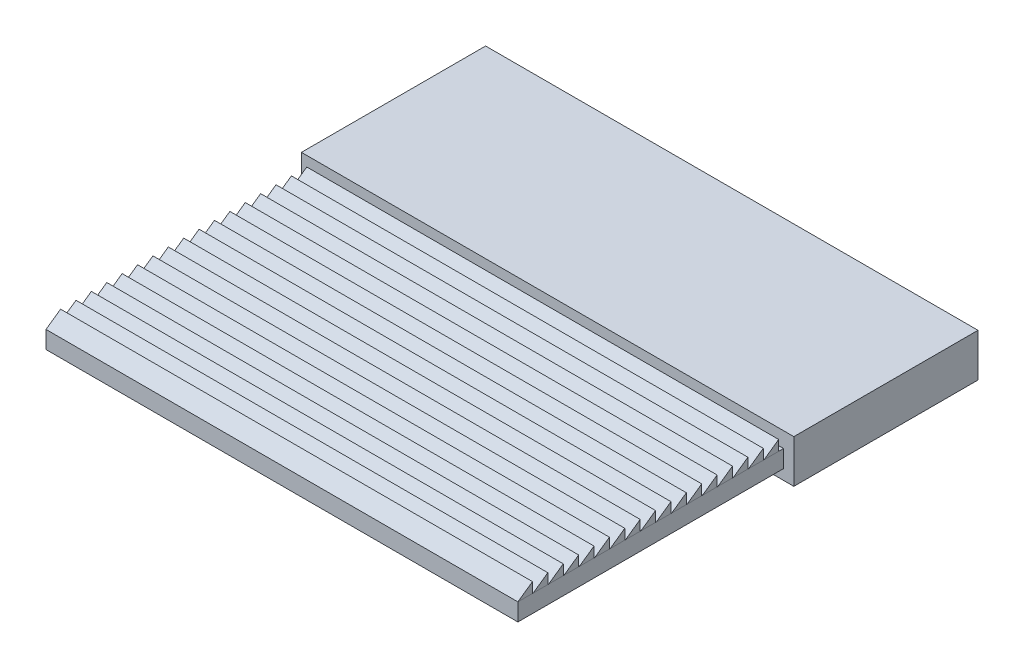
SolidWorks part; units mm, degrees
ref_plane "Front Plane" through (0, 0, 0) normal (0, 0, 1) x (1, 0, 0)
ref_plane "Top Plane" through (0, 0, 0) normal (0, 1, 0) x (1, 0, 0)
ref_plane "Right Plane" through (0, 0, 0) normal (1, 0, 0) x (0, 0, -1)
sketch "Sketch1" plane through (0, 0, 0) normal (0, 1, 0) x (1, 0, 0)
  line L1 (-98.1766, -77.3984) -> (141.8234, -77.3984)
  line L2 (-98.1766, -77.3984) -> (-98.1766, 273.7516)
  line L3 (-98.1766, 273.7516) -> (141.8234, 273.7516)
  line L4 (141.8234, -77.3984) -> (141.8234, 273.7516)
  dimension "D1" = 351.15
  dimension "D2" = 240
extrude "Boss-Extrude3" add sketch "Sketch1" along normal blind 21
sketch "Sketch4" plane through (0, 21, 0) normal (0, 1, 0) x (1, 0, 0)
  line L0 (-98.1766, 54.4816) -> (141.8234, 54.4816)
  line L1 (-98.1766, 273.7516) -> (-98.1766, -77.3984) construction
  line L2 (141.8234, -77.3984) -> (141.8234, 273.7516) construction
  line L3 (-98.1766, -77.3984) -> (141.8234, -77.3984) construction
  line L4 (-98.1766, 183.9816) -> (141.8234, 183.9816)
  line L5 (-98.1766, 183.9816) -> (-98.1766, 54.4816)
  line L6 (141.8234, 54.4816) -> (141.8234, 183.9816)
  dimension "D1" = 131.88
  dimension "D2" = 129.5
ref_plane "Plane4" through (0, 0, -54.4816) normal (0, 0, -1) x (-1, 0, 0)
sketch "Sketch5" plane through (0, 0, -54.4816) normal (0, 0, -1) x (-1, 0, 0)
  line L1 (-145.3358, 60.6964) -> (103.6401, 60.6964)
  line L2 (-145.3358, 60.6964) -> (-145.3358, -52.4745)
  line L3 (-145.3358, -52.4745) -> (103.6401, -52.4745)
  line L4 (103.6401, 60.6964) -> (103.6401, -52.4745)
extrude "Cut-Extrude2" cut sketch "Sketch5" against normal blind 513
extrude "Cut-Extrude3" cut sketch "Sketch4" against normal blind 7.5
sketch "Sketch6" plane through (0, 0, 0) normal (0, -1, 0) x (1, 0, 0)
  line L4 (141.8234, -54.4816) -> (-98.1766, -54.4816)
  line L5 (141.8234, -183.9816) -> (141.8234, -54.4816)
  line L6 (-98.1766, -183.9816) -> (141.8234, -183.9816)
  line L7 (-98.1766, -54.4816) -> (-98.1766, -183.9816)
  line L8 (141.8234, -54.4816) -> (-98.1766, -54.4816)
  line L9 (141.8234, -183.9816) -> (141.8234, -54.4816)
  line L10 (-98.1766, -183.9816) -> (141.8234, -183.9816)
  line L11 (-98.1766, -54.4816) -> (-98.1766, -183.9816)
  dimension "D1" = 0
extrude "Cut-Extrude4" cut sketch "Sketch6" against normal blind 5
sketch "Sketch7" plane through (141.8234, 0, 0) normal (1, 0, 0) x (0, 0, -1)
  line L0 (183.9816, 5) -> (183.9816, 13.5)
  line L1 (183.9816, 13.5) -> (54.4816, 13.5)
  line L2 (54.4816, 13.5) -> (54.4816, 5)
  line L3 (54.4816, 5) -> (183.9816, 5)
sketch "Sketch8" plane through (-98.1766, 0, 0) normal (-1, 0, 0) x (0, 0, 1)
  line L4 (-183.9816, 13.5) -> (-183.9816, 5)
  line L5 (-54.4816, 13.5) -> (-183.9816, 13.5)
  line L6 (-54.4816, 5) -> (-54.4816, 13.5)
  line L7 (-183.9816, 5) -> (-54.4816, 5)
  line L8 (-183.9816, 13.5) -> (-183.9816, 5)
  line L9 (-54.4816, 13.5) -> (-183.9816, 13.5)
  line L10 (-54.4816, 5) -> (-54.4816, 13.5)
  line L11 (-183.9816, 5) -> (-54.4816, 5)
  dimension "D1" = 0
extrude "Cut-Extrude6" cut sketch "Sketch8" against normal blind 5
extrude "Cut-Extrude7" cut sketch "Sketch7" against normal blind 5
sketch "Sketch9" plane through (-98.1766, 0, 0) normal (-1, 0, 0) x (0, 0, 1)
  line L0 (-183.9816, 18.5) -> (-273.7516, 18.5) construction
  line L1 (-183.9816, 0) -> (-183.9816, 21) construction
  line L2 (-273.7516, 21) -> (-273.7516, 0) construction
  line L3 (-273.7516, 21) -> (-183.9816, 21) construction
  dimension "D1" = 2.5
ref_plane "Plane5" through (0, 18.5, 0) normal (0, -1, 0) x (0, 0, -1)
sketch "Sketch13" plane through (0, 18.5, 0) normal (0, -1, 0) x (0, 0, -1)
  line L0 (183.9816, 21.8234) -> (54.4816, 21.8234) construction
  line L1 (183.9816, -98.1766) -> (183.9816, 141.8234) construction
  line L2 (54.4816, 136.8234) -> (54.4816, -93.1766) construction
sketch "Sketch14" plane through (136.8234, 0, 0) normal (1, 0, 0) x (0, 0, -1)
  line L0 (54.4816, 13.5) -> (61.5969, 18.5)
  line L1 (183.9816, 18.5) -> (54.4816, 18.5) construction
  line L2 (61.5969, 18.5) -> (61.5969, 13.5)
  line L3 (183.9816, 13.5) -> (54.4816, 13.5) construction
  line L6 (61.9816, 13.5) -> (69.0969, 18.5)
  line L7 (69.0969, 18.5) -> (69.0969, 13.5)
  line L8 (69.4816, 13.5) -> (76.5969, 18.5)
  line L9 (76.5969, 18.5) -> (76.5969, 13.5)
  line L10 (76.9816, 13.5) -> (84.0969, 18.5)
  line L11 (84.0969, 18.5) -> (84.0969, 13.5)
  line L12 (84.4816, 13.5) -> (91.5969, 18.5)
  line L13 (91.5969, 18.5) -> (91.5969, 13.5)
  line L14 (91.9816, 13.5) -> (99.0969, 18.5)
  line L15 (99.0969, 18.5) -> (99.0969, 13.5)
  line L16 (99.4816, 13.5) -> (106.5969, 18.5)
  line L17 (106.5969, 18.5) -> (106.5969, 13.5)
  line L18 (106.9816, 13.5) -> (114.0969, 18.5)
  line L19 (114.0969, 18.5) -> (114.0969, 13.5)
  line L20 (114.4816, 13.5) -> (121.5969, 18.5)
  line L21 (121.5969, 18.5) -> (121.5969, 13.5)
  line L22 (121.9816, 13.5) -> (129.0969, 18.5)
  line L23 (129.0969, 18.5) -> (129.0969, 13.5)
  line L24 (129.4816, 13.5) -> (136.5969, 18.5)
  line L25 (136.5969, 18.5) -> (136.5969, 13.5)
  line L26 (136.9816, 13.5) -> (144.0969, 18.5)
  line L27 (144.0969, 18.5) -> (144.0969, 13.5)
  line L28 (144.4816, 13.5) -> (151.5969, 18.5)
  line L29 (151.5969, 18.5) -> (151.5969, 13.5)
  line L30 (151.9816, 13.5) -> (159.0969, 18.5)
  line L31 (159.0969, 18.5) -> (159.0969, 13.5)
  line L32 (159.4816, 13.5) -> (166.5969, 18.5)
  line L33 (166.5969, 18.5) -> (166.5969, 13.5)
  line L34 (166.9816, 13.5) -> (174.0969, 18.5)
  line L35 (174.0969, 18.5) -> (174.0969, 13.5)
  line L36 (174.4816, 13.5) -> (181.5969, 18.5)
  line L37 (181.5969, 18.5) -> (181.5969, 13.5)
  line L38 (54.4816, 13.5) -> (181.5969, 13.5)
  line M38 (183.9816, 13.5) -> (54.4816, 13.5)
  dimension "D1" = 17
extrude "Boss-Extrude4" add sketch "Sketch14" along direction (-1, 0, 0) on the side against the normal blind 230 separate body contours L2 L0 M38 | L7 L6 M38 | L9 L8 M38 | L11 L10 M38 | L13 L12 M38 | L15 L14 M38 | L17 L16 M38 | L19 L18 M38 | L21 L20 M38 | L23 L22 M38 | L25 L24 M38 | L27 L26 M38 | L29 L28 M38 | L31 L30 M38 | L33 L32 M38 | L35 L34 M38 | L37 L36 M38
